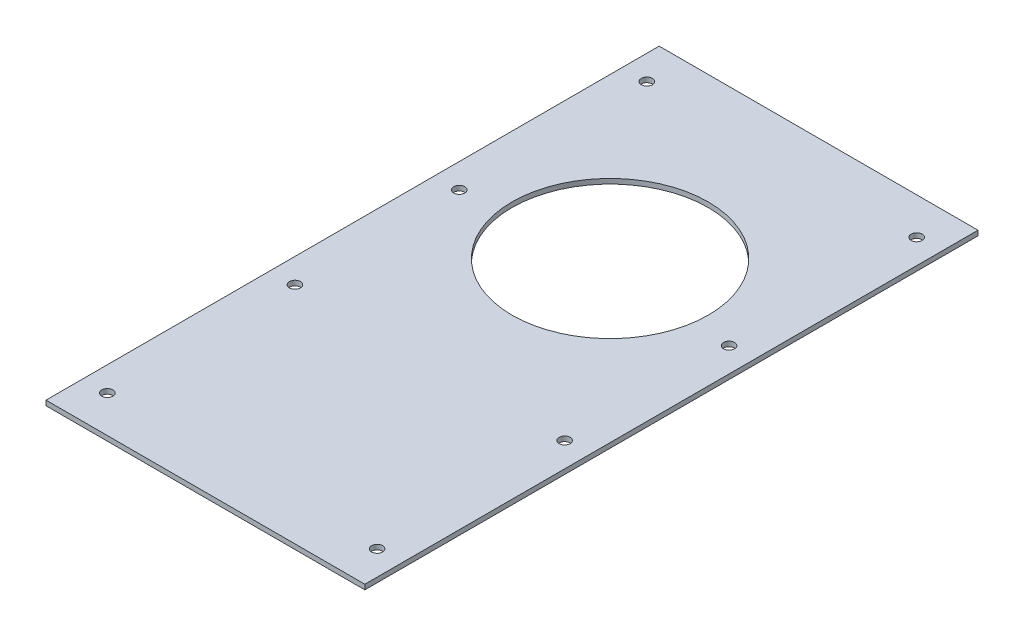
SolidWorks part; units mm, degrees
ref_plane "前视基准面" through (0, 0, 0) normal (0, 0, 1) x (1, 0, 0)
ref_plane "上视基准面" through (0, 0, 0) normal (0, 1, 0) x (1, 0, 0)
ref_plane "右视基准面" through (0, 0, 0) normal (1, 0, 0) x (0, 0, -1)
sketch "草图1" plane through (0, 0, 0) normal (0, 1, 0) x (1, 0, 0)
  line L0 (0, 0) -> (0, 40) construction
  line L1 (-65, 125) -> (65, 125)
  line L2 (-65, 125) -> (-65, -125)
  line L3 (-65, -125) -> (65, -125)
  line L4 (65, 125) -> (65, -125)
  line L5 (-65, 125) -> (65, -125) construction
  line L6 (-65, -125) -> (65, 125) construction
  circle A0 centre (0, 40) radius 40
  point P0 (0, 0)
extrude "凸台-拉伸1" add sketch "草图1" along normal blind 2
hole_wizard "M4 间隙孔1" positions "草图3" profile "草图2" hole size "M4" standard "GB" end condition through all
sketch "草图3" plane through (0, 2, 0) normal (0, 1, 0) x (1, 0, 0)
  line L0 (-65, -105.4592) -> (-55, -105.4592)
  line L1 (-65, 125) -> (-65, -125) construction
  line L3 (-55, -125) -> (-55, -110)
  line L4 (-65, -125) -> (65, -125) construction
  line L5 (-65, 0) -> (65, 0)
  line L6 (65, -125) -> (65, 125) construction
  line L8 (-37.397, 0) -> (-37.397, -33.5)
  line L10 (-55, 125) -> (-55, 110)
  line L11 (65, 125) -> (-65, 125) construction
  point P0 (-55, -110)
  point P2 (-55, -33.5)
sketch "草图2" plane through (-55, 2, 110) normal (1, 0, 0) x (0, 0, 1)
  line L0 (0, 0) -> (0, 2)
  line L1 (0, 2) -> (2.25, 2)
  line L2 (2.25, 2) -> (2.25, 0)
  line L5 (2.25, 0) -> (0, 0)
  line L11 (0, -6.35) -> (0, 107.95) construction
  dimension "通孔孔直径" = 4.5
  dimension "通孔孔深度" = 2
ref_plane "基准面1" through (0, 0, 0) normal (0, 0, 1) x (1, 0, 0)
ref_plane "基准面2" through (0, 0, 0) normal (-1, 0, 0) x (0, 0, 1)
mirror "镜向1" about plane through (0, 0, 0) normal (0, 0, 1) of "M4 间隙孔1"
mirror "镜向2" about plane through (0, 0, 0) normal (-1, 0, 0) of "镜向1", "M4 间隙孔1"
